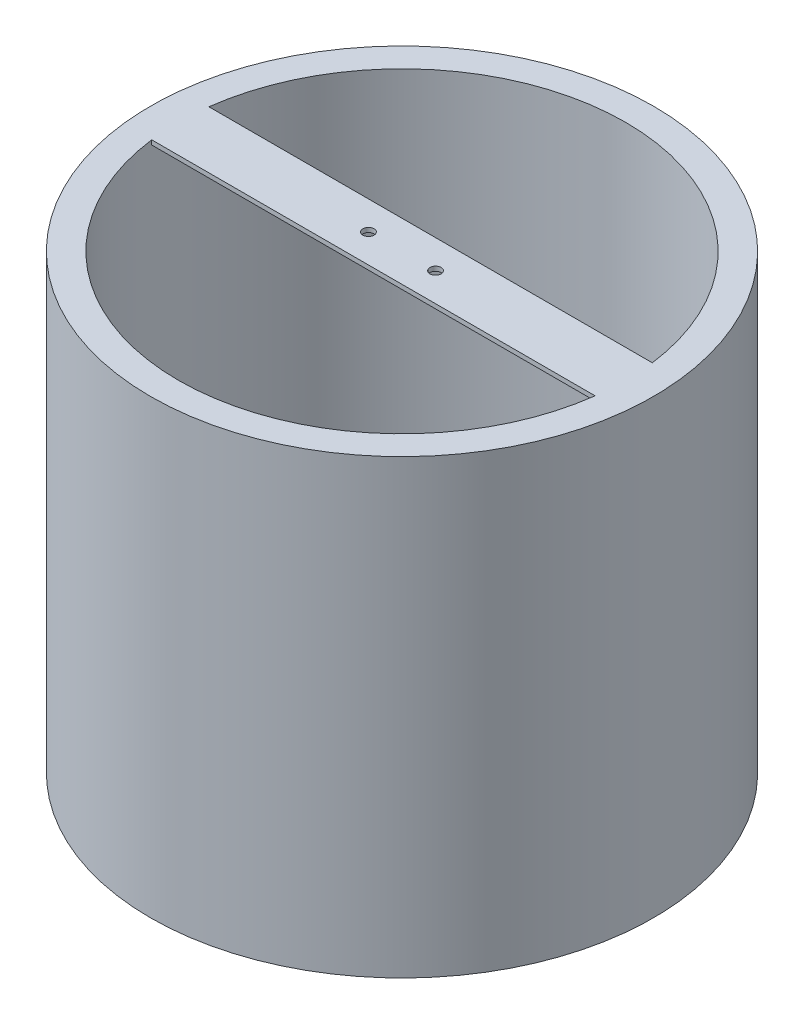
SolidWorks part; units mm, degrees
ref_plane "Front Plane" through (0, 0, 0) normal (0, 0, 1) x (1, 0, 0)
ref_plane "Top Plane" through (0, 0, 0) normal (0, 1, 0) x (1, 0, 0)
ref_plane "Right Plane" through (0, 0, 0) normal (1, 0, 0) x (0, 0, -1)
sketch "Sketch2" plane through (0, 0, 0) normal (0, 1, 0) x (1, 0, 0)
  line L1 (9.3115, 10.6947) -> (49.6615, 10.6947)
  line L2 (9.3115, -10.6947) -> (49.6615, -10.6947)
  line L3 (9.3115, -10.6947) -> (-49.6615, -10.6947)
  line L4 (9.3115, 10.6947) -> (-49.6615, 10.6947)
  circle A0 centre (0, 0) radius 57.15
  circle A1 centre (0, 0) radius 50.8
  arc A2 (-50.7296, 2.6737) -> (-50.7296, -2.6737) centre (0, 0) ccw
  arc A3 (50.7296, 2.6737) -> (50.7296, -2.6737) centre (0, 0) cw
  arc A4 (-49.6615, 10.6947) -> (-49.5679, -11.1206) centre (0, 0) ccw
  arc A5 (49.6615, 10.6947) -> (49.6297, -10.8414) centre (0, 0) cw
  arc A6 (-49.6615, 10.6947) -> (49.6615, 10.6947) centre (0, 0) cw
  arc A7 (-49.6615, -10.6947) -> (49.6615, -10.6947) centre (0, 0) ccw
  point P7 (0, 0)
  point P13 (0, 0)
extrude "Boss-Extrude1" add sketch "Sketch2" along normal blind 101.6 contours A0 | A1
sketch "Sketch4" plane through (0, 101.6, 0) normal (0, 1, 0) x (1, 0, 0)
  line L1 (0, -6.4994) -> (-50.3825, -6.4994)
  line L2 (-59.8292, 6.4994) -> (50.3825, 6.4994)
  line L3 (0, -6.4994) -> (50.3825, -6.4994)
  circle A0 centre (0, 0) radius 50.8 construction
  arc A1 (50.3825, 6.4994) -> (-50.3825, 6.4994) centre (0, 0) ccw
  arc A2 (50.3825, -6.4994) -> (-50.3825, -6.4994) centre (0, 0) cw
  circle A3 centre (0, 0) radius 63.5
  point P4 (0, 0)
  point P11 (-4.7234, 6.4994)
  circle M1 centre (0, 0) radius 57.15
  circle M2 centre (0, 0) radius 50.8
extrude "Boss-Extrude2" add sketch "Sketch4" along normal blind 1.016 contours L1 L3 L2 M2 | M1 M2
sketch "Sketch5" plane through (0, 102.616, 0) normal (0, 1, 0) x (1, 0, 0)
  circle A0 centre (7.62, 0) radius 1.27
  circle A1 centre (-7.62, 0) radius 1.27
  point P4 (0, 0)
sketch "Sketch6" plane through (0, 102.616, 0) normal (0, 1, 0) x (1, 0, 0)
  point P4 (0, 0)
extrude "Cut-Extrude2" cut sketch "Sketch5" against normal blind 14.732 contours A1 | A0
